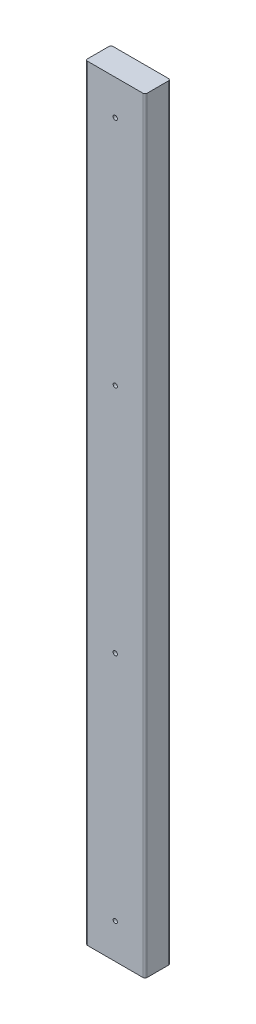
SolidWorks part; units mm, degrees
ref_plane "Front" through (0, 0, 0) normal (0, 0, 1) x (1, 0, 0)
ref_plane "Top" through (0, 0, 0) normal (0, 1, 0) x (1, 0, 0)
ref_plane "Right" through (0, 0, 0) normal (1, 0, 0) x (0, 0, -1)
sketch "Sketch1" plane through (0, 0, 0) normal (0, 1, 0) x (1, 0, 0)
  line L1 (44.45, 19.05) -> (-44.45, 19.05)
  line L2 (44.45, 19.05) -> (44.45, -19.05)
  line L3 (44.45, -19.05) -> (-44.45, -19.05)
  line L4 (-44.45, 19.05) -> (-44.45, -19.05)
  line L5 (44.45, 19.05) -> (-44.45, -19.05) construction
  line L6 (44.45, -19.05) -> (-44.45, 19.05) construction
  point P0 (0, 0)
  dimension "D1" = 38.1
  dimension "D2" = 88.9
extrude "Boss-Extrude1" add sketch "Sketch1" along normal blind 1143
hole_wizard "1/4 (0.25) Diameter Hole1" positions "Sketch3" profile "Sketch4" hole size "1/4" standard "ANSI Inch" end condition through all
sketch "Sketch3" plane through (0, 0, -19.05) normal (0, 0, -1) x (-1, 0, 0)
  line L0 (-44.45, 0) -> (44.45, 0) construction
  point P0 (0, 52.3875)
  point P12 (0, 0)
  point P30 (0, 398.4625)
  point P31 (0, 744.5375)
  point P32 (0, 1090.6125)
  dimension "D1" = 52.3875
  dimension "D2" = 4
sketch "Sketch4" plane through (0, 52.3875, -19.05) normal (1, 0, 0) x (0, 1, 0)
  line L0 (0, 0) -> (0, 38.1)
  line L1 (0, 38.1) -> (3.175, 38.1)
  line L2 (3.175, 38.1) -> (3.175, 0)
  line L5 (3.175, 0) -> (0, 0)
  line L11 (0, -6.35) -> (0, 107.95) construction
  dimension "Thru Hole Dia." = 6.35
  dimension "Thru Hole Depth" = 38.1
fillet "Fillet1" radius 3.175 4 edges at (-44.45, 571.5, 19.05) (-44.45, 571.5, -19.05) (44.45, 571.5, 19.05) (44.45, 571.5, -19.05)
